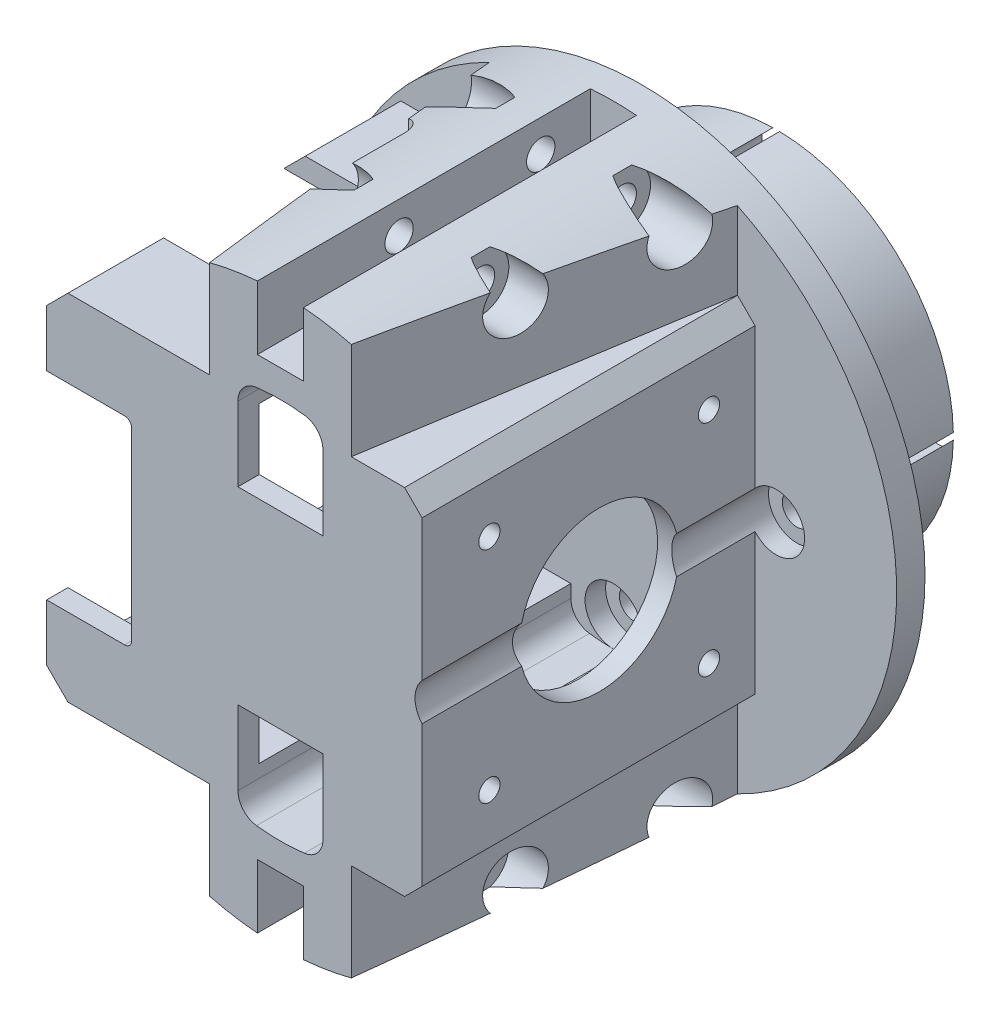
SolidWorks part; units mm, degrees
ref_plane "前视基准面" through (0, 0, 0) normal (0, 0, 1) x (1, 0, 0)
ref_plane "上视基准面" through (0, 0, 0) normal (0, 1, 0) x (1, 0, 0)
ref_plane "右视基准面" through (0, 0, 0) normal (1, 0, 0) x (0, 0, -1)
other "Configuration Table"
sketch "草图1" plane through (0, 0, 0) normal (0, 0, 1) x (1, 0, 0)
  circle A10 centre (0, 0) radius 24 construction
  circle A11 centre (0, 0) radius 25
  point P15 (0, 0)
  dimension "D1" = 50
  dimension "D2" = 48
extrude "凸台-拉伸1" add sketch "草图1" along normal blind 13
sketch "草图3" plane through (0, 0, 13) normal (0, 0, 1) x (1, 0, 0)
  circle A0 centre (0, 0) radius 40
  dimension "D1" = 80
extrude "凸台-拉伸3" add sketch "草图3" along normal blind 4
sketch "草图4" plane through (0, 0, 17) normal (0, 0, 1) x (1, 0, 0)
  line L0 (0, 0) -> (-8, 0) construction
  line L1 (-33, 22) -> (-30, 25)
  line L2 (-33, 22) -> (17, 22) construction
  line L3 (-33, 22) -> (-33, -22) construction
  line L4 (-33, -22) -> (17, -22) construction
  line L5 (17, 22) -> (17, -22) construction
  line L6 (-33, 22) -> (17, -22) construction
  line L7 (-33, -22) -> (17, 22) construction
  line L8 (-30, 25) -> (17.5251, 25)
  line L9 (17.5251, 25) -> (20, 22.5251)
  line L10 (20, 22.5251) -> (20, -22.5251)
  line L11 (20, -22.5251) -> (17.5251, -25)
  line L12 (17.5251, -25) -> (-30, -25)
  line L13 (-30, -25) -> (-33, -22)
  line L14 (-33, -22) -> (17, -22)
  line L15 (17, -22) -> (17, 22)
  line L16 (17, 22) -> (-33, 22)
  dimension "D1" = 8
  dimension "D2" = 50
  dimension "D3" = 44
  dimension "D4" = 45
  dimension "D5" = 3
  dimension "D6" = 3
  dimension "D7" = 3
  dimension "D8" = 3.5
  dimension "D9" = 3.5
  dimension "D10" = 45
extrude "凸台-拉伸4" add sketch "草图4" along normal blind 44
sketch "草图5" plane through (0, 0, 61) normal (0, 0, 1) x (1, 0, 0)
  line L0 (-33, 22) -> (-33, 14)
  line L1 (0, 0) -> (-33, 0) construction
  line L2 (-33, 14) -> (-21, 14)
  line L3 (-21, 14) -> (-21, -14)
  line L4 (-33, -14) -> (-21, -14)
  line L5 (-33, -14) -> (-33, -22)
  line L10 (17, 22) -> (17, -22)
  line L11 (17, -22) -> (-33, -22)
  line L12 (-33, -22) -> (-30, -25)
  line L13 (-30, -25) -> (17.5251, -25)
  line L14 (17.5251, -25) -> (20, -22.5251)
  line L15 (20, -22.5251) -> (20, 22.5251)
  line L16 (20, 22.5251) -> (17.5251, 25)
  line L17 (17.5251, 25) -> (-30, 25)
  line L18 (-30, 25) -> (-33, 22)
  line L19 (-33, 22) -> (17, 22)
  line L22 (-33, -22) -> (-30, -25)
  line L23 (-30, -25) -> (17.5251, -25)
  line L24 (17.5251, -25) -> (20, -22.5251)
  line L25 (20, -22.5251) -> (20, 22.5251)
  line L26 (20, 22.5251) -> (17.5251, 25)
  line L27 (17.5251, 25) -> (-30, 25)
  line L28 (-30, 25) -> (-33, 22)
  point P14 (-21, 0)
  dimension "D2" = 28
  dimension "D3" = 12
  dimension "D1" = 0
extrude "凸台-拉伸5" add sketch "草图5" along normal blind 3
sketch "草图8" plane through (0, 25, 0) normal (0, 1, 0) x (1, 0, 0)
  line L0 (0, -17) -> (0, -64) construction
  line L1 (17.5251, -17) -> (-30, -17) construction
  line L2 (17.5251, -64) -> (-30, -64) construction
  line L3 (-3.25, -17) -> (-3.25, -64) construction
  line L4 (-3.25, -17) -> (3.25, -17)
  line L5 (-3.25, -64) -> (3.25, -64)
  line L6 (3.25, -64) -> (3.25, -17) construction
  line L7 (-3.25, -17) -> (-17.5, -17)
  line L8 (-17.5, -17) -> (-10, -64)
  line L9 (-10, -64) -> (-3.25, -64)
  line L10 (10, -64) -> (3.25, -64)
  line L11 (17.5, -17) -> (10, -64)
  line L12 (3.25, -17) -> (17.5, -17)
  point P7 (0, -17)
  dimension "D1" = 17.5
  dimension "D2" = 6.5
  dimension "D3" = 10
extrude "凸台-拉伸6" add sketch "草图8" along normal blind 15
sketch "草图9" plane through (0, 40, 0) normal (0, 1, 0) x (1, 0, 0)
  line L5 (10, -64) -> (17.5, -17)
  line L6 (17.5, -17) -> (0, -17)
  line L7 (0, -17) -> (-17.5, -17)
  line L8 (-17.5, -17) -> (-10, -64)
  line L9 (-10, -64) -> (10, -64)
  line L10 (10, -64) -> (17.5, -17)
  line L11 (17.5, -17) -> (0, -17)
  line L12 (0, -17) -> (-17.5, -17)
  line L13 (-17.5, -17) -> (-10, -64)
  line L14 (-10, -64) -> (10, -64)
  dimension "D1" = 0
extrude "凸台-拉伸7" add sketch "草图9" against normal blind 15 from surface at -65 starting at face at (-6.2374, -25, 40.5)
sketch "草图10" plane through (0, 0, 64) normal (0, 0, 1) x (1, 0, 0)
  line L0 (0, 0) -> (0, -20.7494) construction
  line L5 (0, -30.8678) -> (0, -40) construction
  line L6 (0, 0) -> (20, 0) construction
  line L8 (-3.25, -30.8678) -> (3.25, -30.8678)
  line L9 (16.0328, 36.6463) -> (17.5, 40) construction
  line L11 (-3.25, -30.8678) -> (-3.25, -39.8678)
  line L22 (3.25, -30.8678) -> (3.25, -39.8678)
  line L23 (-3.25, -30.8678) -> (3.25, -39.8678) construction
  line L24 (-3.25, -39.8678) -> (3.25, -30.8678) construction
  line L25 (20, -22.5251) -> (20, 22.5251) construction
  line L26 (-17.5, -35.9687) -> (-17.5, -40)
  line L29 (-17.5, -40) -> (17.5, -40)
  line L31 (-17.5, 40) -> (0, 0) construction
  line L32 (-17.5, -40) -> (-16.0328, -36.6463) construction
  line L33 (-17.5, 40) -> (-16.0328, 36.6463) construction
  line L34 (16.0328, -36.6463) -> (17.5, -40) construction
  line L35 (17.5, -35.9687) -> (17.5, -40)
  line L36 (-3.25, 39.8678) -> (3.25, 30.8678) construction
  line L37 (-3.25, 30.8678) -> (3.25, 39.8678) construction
  line L38 (0, 30.8678) -> (0, 40) construction
  line L39 (17.5, 35.9687) -> (17.5, 40)
  line L40 (-17.5, 40) -> (17.5, 40)
  line L41 (-17.5, 35.9687) -> (-17.5, 40)
  line L42 (3.25, 30.8678) -> (3.25, 39.8678)
  line L43 (-3.25, 30.8678) -> (-3.25, 39.8678)
  line L44 (-3.25, 30.8678) -> (3.25, 30.8678)
  arc A5 (-17.5, -35.9687) -> (-3.25, -39.8678) centre (0, 0) ccw
  arc A7 (3.25, -39.8678) -> (17.5, -35.9687) centre (0, 0) ccw
  arc A8 (3.25, 39.8678) -> (17.5, 35.9687) centre (0, 0) cw
  arc A9 (-17.5, 35.9687) -> (-3.25, 39.8678) centre (0, 0) cw
  point P3 (0, -35.3678)
  point P32 (0, 35.3678)
  dimension "D1" = 9
  dimension "D3" = 40
  dimension "D2" = 6.5
extrude "切除-拉伸7" cut sketch "草图10" against normal blind 47
sketch "草图15" plane through (-33, 0, 0) normal (-1, 0, 0) x (0, 0, 1)
  line L0 (17, -35.9687) -> (17, -25) construction
  line L1 (64, -39.8678) -> (17, -39.8678) construction
  line L2 (64, -39.8678) -> (64, -30.8678) construction
  line L3 (64, -30.8678) -> (17, -30.8678) construction
  line L4 (17, -39.8678) -> (17, -30.8678) construction
  line L5 (0, 0) -> (64, 0) construction
  line L6 (64, 14) -> (64, -14) construction
  line L7 (17, -35.3678) -> (64, -35.3678) construction
  line L8 (17, 35.3678) -> (64, 35.3678) construction
  line L9 (17, 39.8678) -> (17, 30.8678) construction
  line L10 (64, 30.8678) -> (17, 30.8678) construction
  line L11 (64, 39.8678) -> (64, 30.8678) construction
  line L12 (64, 39.8678) -> (17, 39.8678) construction
  circle A0 centre (24, -35.3678) radius 2
  circle A1 centre (44, -35.3678) radius 2
  circle A3 centre (44, 35.3678) radius 2
  circle A4 centre (24, 35.3678) radius 2
  dimension "D2" = 7
  dimension "D3" = 4
  dimension "D4" = 4
  dimension "D1" = 9
  dimension "D5" = 27
extrude "切除-拉伸8" cut sketch "草图15" against normal up to surface (53 mm away) up to face at (20, 0, 40.5)
sketch "草图17" plane through (-33, 0, 0) normal (-1, 0, 0) x (0, 0, 1)
  circle A0 centre (44, -35.3678) radius 4
  circle A1 centre (24, -35.3678) radius 4
  circle A2 centre (24, 35.3678) radius 4
  circle A3 centre (44, 35.3678) radius 4
  dimension "D1" = 8
  dimension "D2" = 8
  dimension "D3" = 8
  dimension "D4" = 8
extrude "切除-拉伸9" cut sketch "草图17" against normal offset from surface (24.75 mm away) 5 contours A2 | A3 | A1 | A0 up to face at (-3.25, -37.3678, 44)
sketch "草图18" plane through (20, 0, 0) normal (1, 0, 0) x (0, 0, -1)
  circle A0 centre (-44, 35.3678) radius 4
  circle A1 centre (-24, 35.3678) radius 4
  circle A2 centre (-44, -35.3678) radius 4
  circle A3 centre (-24, -35.3678) radius 4
  dimension "D1" = 8
  dimension "D2" = 8
  dimension "D3" = 8
  dimension "D4" = 8
extrude "切除-拉伸10" cut sketch "草图18" against normal offset from surface (11.75 mm away) 5 up to face at (3.25, -33.3678, 44)
sketch "草图19" plane through (17, 0, 0) normal (-1, 0, 0) x (0, 0, 1)
  line L0 (61, 0) -> (17, 0) construction
  line L1 (39, 22) -> (39, -22) construction
  line L3 (23.5, 15.5) -> (54.5, 15.5) construction
  line L4 (17, 22) -> (17, -22)
  line L5 (17, -22) -> (61, -22)
  line L6 (61, -22) -> (61, 22)
  line L7 (61, 22) -> (17, 22)
  line L8 (17, 22) -> (17, -22) construction
  line L9 (17, -22) -> (61, -22) construction
  line L10 (61, -22) -> (61, 22) construction
  line L11 (61, 22) -> (17, 22) construction
  line L12 (23.5, 15.5) -> (23.5, -15.5) construction
  line L13 (23.5, -15.5) -> (54.5, -15.5) construction
  line L14 (54.5, 15.5) -> (54.5, -15.5) construction
  line L15 (23.5, 15.5) -> (54.5, -15.5) construction
  line L16 (23.5, -15.5) -> (54.5, 15.5) construction
  circle A0 centre (54.5, 15.5) radius 1.5
  circle A1 centre (23.5, 15.5) radius 1.5
  circle A2 centre (23.5, -15.5) radius 1.5
  circle A3 centre (54.5, -15.5) radius 1.5
  circle A4 centre (39, 0) radius 11.25
  point P8 (39, 0)
  dimension "D4" = 3
  dimension "D7" = 22.5
  dimension "D2" = 31
  dimension "D3" = 31
  dimension "D1" = 0
  dimension "D5" = 2
  dimension "D6" = 2
extrude "切除-拉伸11" cut sketch "草图19" against normal blind 3 contours A4 | A1 | A0 | A2 | A3
sketch "草图21" plane through (0, 0, 64) normal (0, 0, 1) x (1, 0, 0)
  line L0 (0, 0) -> (20, 0) construction
  line L1 (20, -22.5251) -> (20, 22.5251) construction
  line L2 (-6, -13.3249) -> (6, -13.3249)
  line L8 (-6, 26.3249) -> (-6, 18.3249)
  line L9 (0, 0) -> (0, 15.9189) construction
  line L10 (6, 26.3249) -> (6, 18.3249)
  line L11 (6, -26.3249) -> (6, -18.3249)
  line L12 (-6, -26.3249) -> (-6, -18.3249)
  line L14 (-6, 18.3249) -> (-6, 13.3249)
  line L15 (-6, 13.3249) -> (6, 13.3249)
  line L16 (6, 18.3249) -> (6, 13.3249)
  line L17 (6, -18.3249) -> (6, -13.3249)
  line L19 (-6, -18.3249) -> (-6, -13.3249)
  circle A1 centre (0, 24) radius 1.5 construction
  circle A2 centre (24, 0) radius 1.5 construction
  circle A3 centre (0, -24) radius 1.5 construction
  arc A5 (6, 26.3249) -> (-6, 26.3249) centre (0, 0) ccw
  arc A6 (6, 22.9565) -> (-6, 22.9565) centre (0, 0) ccw construction
  arc A7 (23.9531, -1.4993) -> (23.9531, 1.4993) centre (0, 0) ccw construction
  arc A8 (-1.4993, -23.9531) -> (1.4993, -23.9531) centre (0, 0) ccw construction
  arc A9 (-23.9531, -1.4993) -> (-23.9531, 1.4993) centre (-24, 0) ccw construction
  arc A10 (6, -22.9565) -> (-6, -22.9565) centre (0, 0) cw construction
  circle A11 centre (0, -24) radius 1.5 construction
  arc A12 (6, -26.3249) -> (-6, -26.3249) centre (0, 0) cw
  circle A13 centre (24, 0) radius 4
  point P17 (0, 0)
  dimension "D1" = 8
  dimension "D2" = 3
  dimension "D6" = 54
  dimension "D4" = 5
  dimension "D5" = 8
  dimension "D7" = 6
  dimension "D3" = 4
extrude "切除-拉伸15" cut sketch "草图21" against normal up to surface (47 mm away) up to face at (-18.45, 0, 17)
fillet "圆角1" radius 3 4 edges at (-6, -26.3249, 40.5) (6, -26.3249, 40.5) (-6, 26.3249, 40.5) (6, 26.3249, 40.5)
sketch "草图6" plane through (0, 0, 0) normal (0, 0, -1) x (-1, 0, 0)
  circle A0 centre (0, 0) radius 23 construction
  circle A1 centre (0, 23) radius 2.05
  circle A2 centre (23, 0) radius 2.05
  circle A3 centre (0, -23) radius 2.05
  circle A4 centre (-23, 0) radius 2.05
  point P14 (0, 0)
  dimension "D1" = 46
  dimension "D2" = 4.1
  dimension "D3" = 4
extrude "切除-拉伸16" cut sketch "草图6" against normal up to surface (17 mm away) up to face at (20.9438, 0, 17)
sketch "草图27" plane through (0, 0, 0) normal (0, 0, -1) x (-1, 0, 0)
  circle A0 centre (0, 0) radius 13.5
  dimension "D1" = 27
extrude "切除-拉伸17" cut sketch "草图27" against normal blind 14
sketch "草图28" plane through (0, 0, 64) normal (0, 0, 1) x (1, 0, 0)
  circle A0 centre (23, 0) radius 4
  dimension "D1" = 8
extrude "切除-拉伸18" cut sketch "草图28" against normal up to surface (47 mm away) up to face at (25.05, 0, 17)
sketch "草图29" plane through (0, 0, 17) normal (0, 0, 1) x (1, 0, 0)
  circle A0 centre (23, 0) radius 4
  circle A1 centre (0, -23) radius 4
  circle A2 centre (-23, 0) radius 4
  circle A3 centre (0, 23) radius 4
  point P12 (0, 0)
  dimension "D1" = 8
  dimension "D2" = 4
extrude "切除-拉伸21" cut sketch "草图29" against normal blind 2.9 contours A0 | A3 | A2 | A1
sketch "草图30" plane through (0, -25, 0) normal (0, -1, 0) x (1, 0, 0)
  line L6 (-33, 64) -> (-33, 17) construction
  line L7 (-33, 40.5) -> (-23, 40.5) construction
  line L9 (-13, 50.5) -> (-33, 50.5)
  line L10 (-13, 50.5) -> (-13, 30.5)
  line L11 (-13, 30.5) -> (-33, 30.5)
  line L12 (-33, 50.5) -> (-33, 30.5)
  line L13 (-13, 50.5) -> (-33, 30.5) construction
  line L14 (-13, 30.5) -> (-33, 50.5) construction
  dimension "D1" = 10
  dimension "D2" = 20
extrude "切除-拉伸22" cut sketch "草图30" against normal through all and the other way through all
fillet "圆角2" radius 3 2 edges at (-13, -29.9143, 30.5) (-13, 29.9143, 30.5)
fillet "圆角3" radius 1 2 edges at (-21, -14, 62.5) (-21, 14, 62.5)
sketch "草图31" plane through (0, 0, 13) normal (0, 0, -1) x (-1, 0, 0)
  circle A0 centre (0, 0) radius 25
  circle A1 centre (0, 0) radius 28
  dimension "D1" = 50
  dimension "D2" = 56
extrude "凸台-拉伸8" add sketch "草图31" along normal blind 3
sketch "草图32" plane through (0, 0, 0) normal (0, 0, -1) x (-1, 0, 0)
  circle A0 centre (0, 0) radius 13.5 construction
  circle A1 centre (0, 0) radius 13.5
  arc A8 (24.9956, 0.4691) -> (0.4691, 24.9956) centre (0, 0) ccw
  arc A9 (-0.4691, 24.9956) -> (0.4691, 24.9956) centre (0, 23) ccw
  arc A10 (-0.4691, 24.9956) -> (-24.9956, 0.4691) centre (0, 0) ccw
  arc A11 (-24.9956, -0.4691) -> (-24.9956, 0.4691) centre (-23, 0) ccw
  arc A12 (-24.9956, -0.4691) -> (-0.4691, -24.9956) centre (0, 0) ccw
  arc A13 (0.4691, -24.9956) -> (-0.4691, -24.9956) centre (0, -23) ccw
  arc A14 (0.4691, -24.9956) -> (24.9956, -0.4691) centre (0, 0) ccw
  arc A15 (24.9956, 0.4691) -> (24.9956, -0.4691) centre (23, 0) ccw
  arc A16 (24.9956, 0.4691) -> (0.4691, 24.9956) centre (0, 0) ccw
  arc A17 (-0.4691, 24.9956) -> (0.4691, 24.9956) centre (0, 23) ccw
  arc A18 (-0.4691, 24.9956) -> (-24.9956, 0.4691) centre (0, 0) ccw
  arc A19 (-24.9956, -0.4691) -> (-24.9956, 0.4691) centre (-23, 0) ccw
  arc A20 (-24.9956, -0.4691) -> (-0.4691, -24.9956) centre (0, 0) ccw
  arc A21 (0.4691, -24.9956) -> (-0.4691, -24.9956) centre (0, -23) ccw
  arc A22 (0.4691, -24.9956) -> (24.9956, -0.4691) centre (0, 0) ccw
  arc A23 (24.9956, 0.4691) -> (24.9956, -0.4691) centre (23, 0) ccw
  dimension "D1" = 0
extrude "凸台-拉伸9" add sketch "草图32" along normal blind 6
